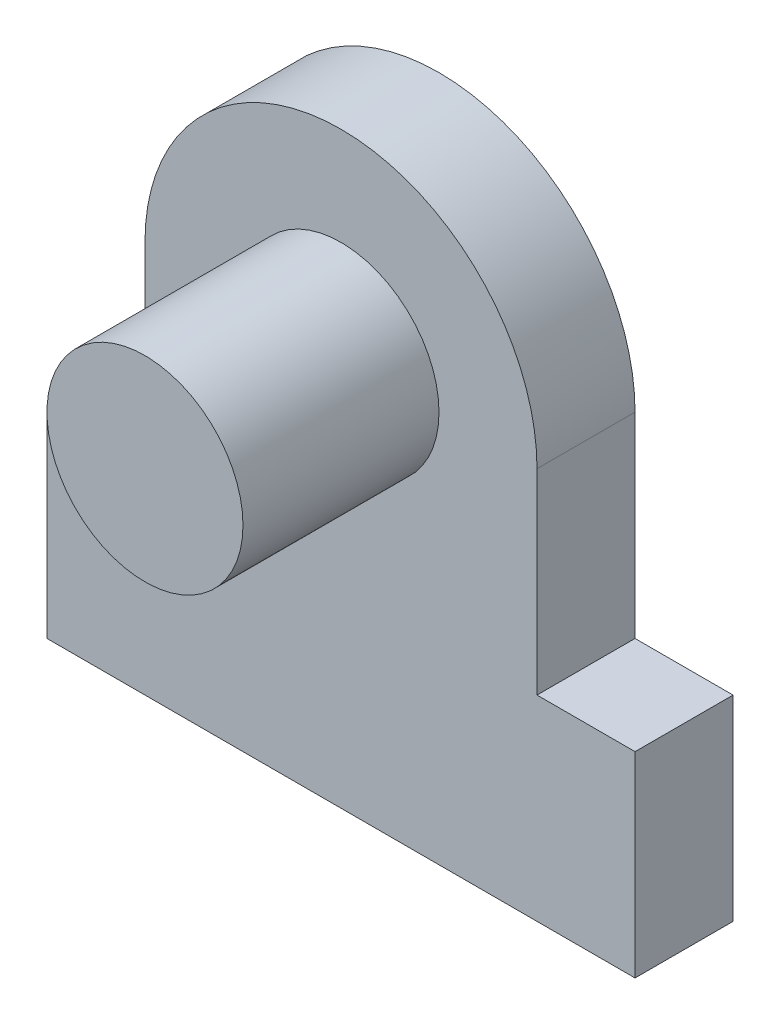
SolidWorks part; units mm, degrees
material "1.0037 (S235JR)"
ref_plane "Plan de face" through (0, 0, 0) normal (0, 0, 1) x (1, 0, 0)
ref_plane "Plan de dessus" through (0, 0, 0) normal (0, 1, 0) x (1, 0, 0)
ref_plane "Plan de droite" through (0, 0, 0) normal (1, 0, 0) x (0, 0, -1)
sketch "Esquisse1" plane through (0, 0, 0) normal (0, 0, 1) x (1, 0, 0)
  line L0 (0, 40) -> (0, 0) construction
  line L1 (-30, 0) -> (30, 0)
  line L2 (30, 0) -> (30, 20)
  line L3 (30, 20) -> (20, 20)
  line L4 (20, 20) -> (20, 40)
  line L5 (-30, 0) -> (-30, 20)
  line L6 (-30, 20) -> (-20, 20)
  line L7 (-20, 20) -> (-20, 40)
  arc A0 (20, 40) -> (-20, 40) centre (0, 40) ccw
  dimension "D1" = 60
  dimension "D2" = 20
  dimension "D3" = 10
  dimension "D4" = 20
extrude "Boss.-Extru.1" add sketch "Esquisse1" along normal blind 10
sketch "Esquisse2" plane through (0, 0, 10) normal (0, 0, 1) x (1, 0, 0)
  circle A0 centre (0, 40) radius 10
  dimension "D1" = 20
extrude "Boss.-Extru.2" add sketch "Esquisse2" along normal blind 20
